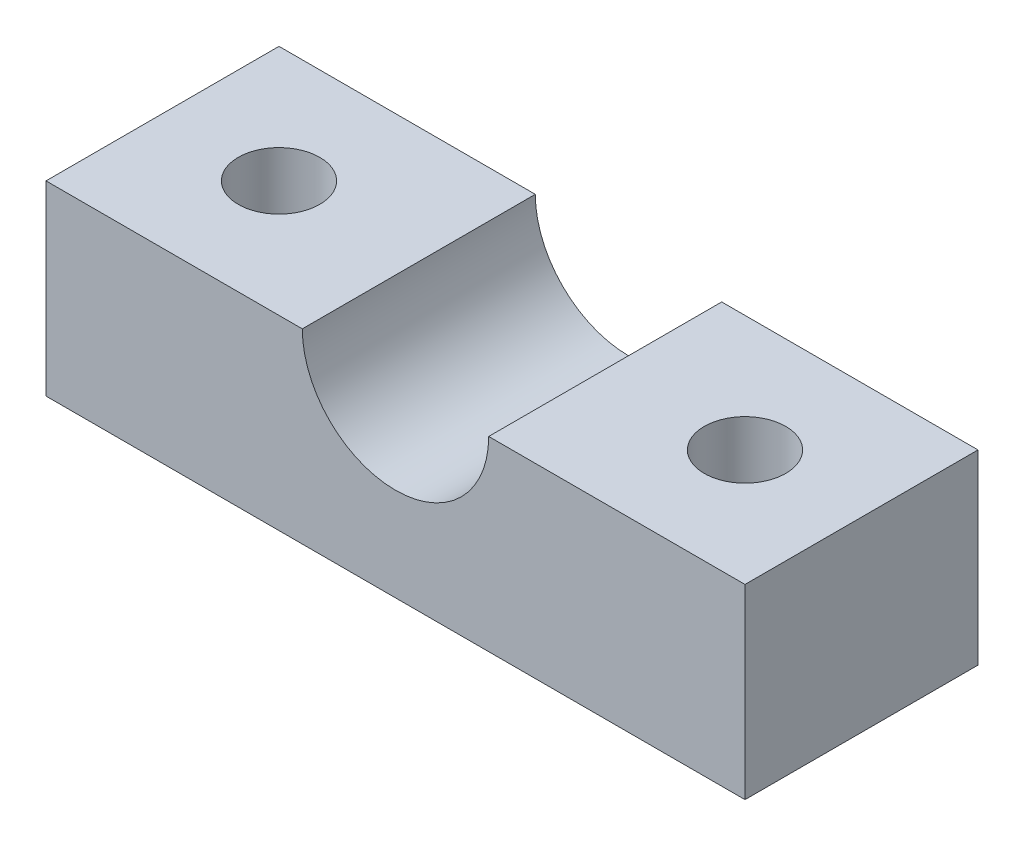
SolidWorks part; units mm, degrees
ref_plane "Ebene vorne" through (0, 0, 0) normal (0, 0, 1) x (1, 0, 0)
ref_plane "Ebene oben" through (0, 0, 0) normal (0, 1, 0) x (1, 0, 0)
ref_plane "Ebene rechts" through (0, 0, 0) normal (1, 0, 0) x (0, 0, -1)
sketch "Skizze1" plane through (0, 0, 0) normal (0, 0, 1) x (1, 0, 0)
  line L0 (19, 8) -> (30, 8)
  line L1 (0, 0) -> (30, 0)
  line L2 (0, 0) -> (0, 8)
  line L3 (0, 8) -> (11, 8)
  line L4 (30, 0) -> (30, 8)
  arc A0 (11, 8) -> (19, 8) centre (15, 8) ccw
  dimension "D4" = 8
  dimension "D1" = 30
  dimension "D2" = 8
  dimension "D3" = 15
extrude "Aufsatz-Linear austragen1" add sketch "Skizze1" along normal blind 10
hole_wizard "Ø3.5 (3.5) Durchmesser Bohrung2" positions "Skizze4" profile "Skizze5" hole size "Ø3.5" standard "DIN" end condition up to next
sketch "Skizze4" plane through (0, 0, 0) normal (0, -1, 0) x (-1, 0, 0)
  line L0 (0, -10) -> (-30, -10) construction
  line L2 (-30, -10) -> (-30, 0) construction
  line L3 (0, -10) -> (0, 0) construction
  point P0 (-5, -5)
  point P2 (-25, -5)
  point P11 (-30, -6.9861)
  dimension "D1" = 5
  dimension "D2" = 5
  dimension "D3" = 5
  dimension "D4" = 5
sketch "Skizze5" plane through (5, 0, 5) normal (1, 0, 0) x (0, 0, -1)
  line L0 (0, 0) -> (0, 8)
  line L1 (0, 8) -> (1.75, 8)
  line L2 (1.75, 8) -> (1.75, 0)
  line L5 (1.75, 0) -> (0, 0)
  line L11 (0, -6.35) -> (0, 107.95) construction
  dimension "Bohrerdurchmesser" = 3.5
  dimension "Bohrungstiefe" = 8
